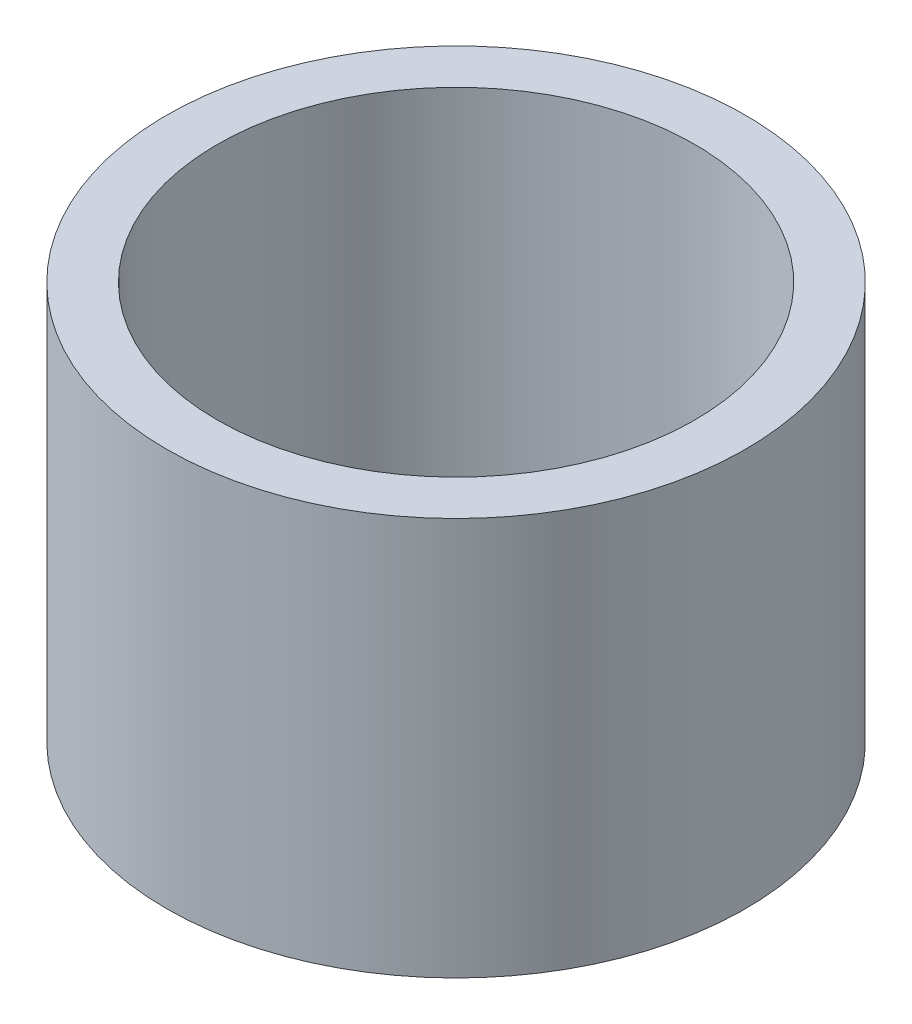
SolidWorks part; units mm, degrees
ref_plane "Front Plane" through (0, 0, 0) normal (0, 0, 1) x (1, 0, 0)
ref_plane "Top Plane" through (0, 0, 0) normal (0, 1, 0) x (1, 0, 0)
ref_plane "Right Plane" through (0, 0, 0) normal (1, 0, 0) x (0, 0, -1)
sketch "Sketch1" plane through (0, 0, 0) normal (0, 1, 0) x (1, 0, 0)
  circle A0 centre (0, 0) radius 3.3
  circle A1 centre (0, 0) radius 4
  dimension "D1" = 6.6
  dimension "D2" = 8
extrude "Boss-Extrude1" add sketch "Sketch1" along normal blind 5.5
